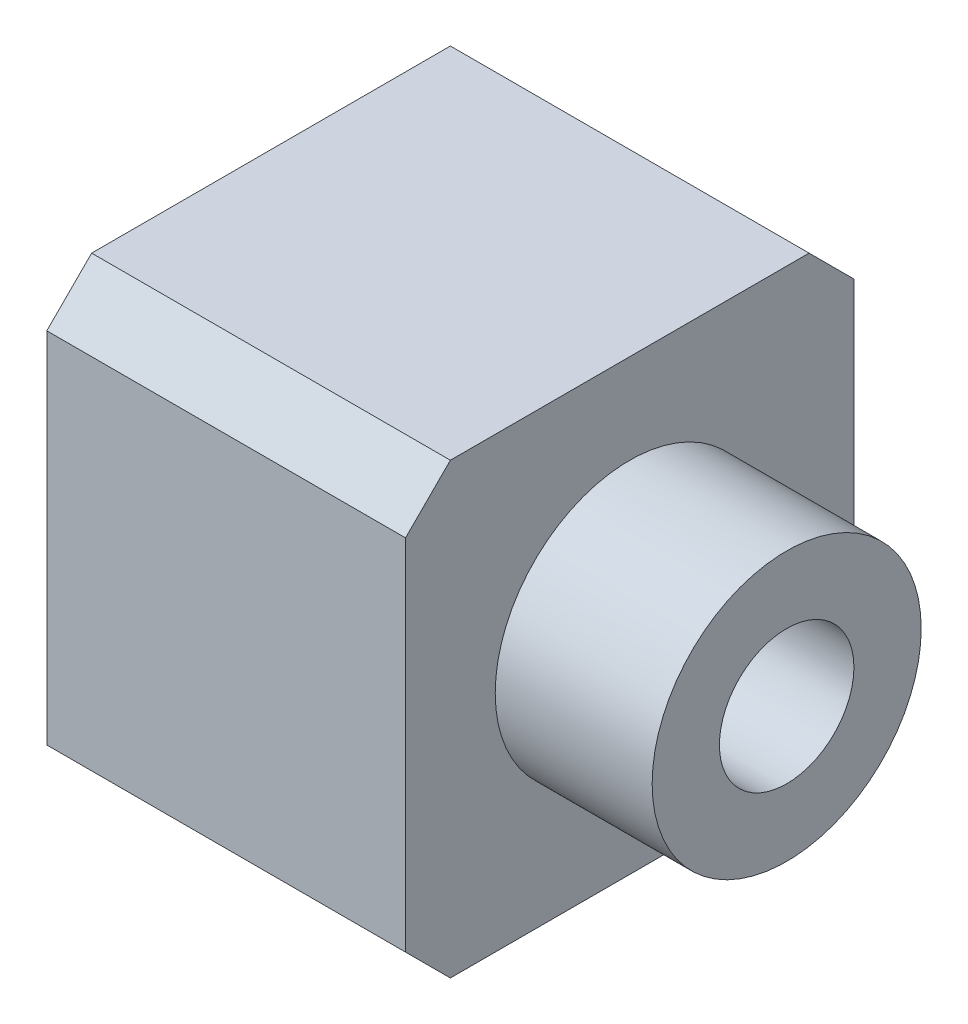
SolidWorks part; units mm, degrees
ref_plane "Front Plane" through (0, 0, 0) normal (0, 0, 1) x (1, 0, 0)
ref_plane "Top Plane" through (0, 0, 0) normal (0, 1, 0) x (1, 0, 0)
ref_plane "Right Plane" through (0, 0, 0) normal (1, 0, 0) x (0, 0, -1)
sketch "Sketch1" plane through (0, 0, 0) normal (1, 0, 0) x (0, 0, -1)
  line L5 (5, -5) -> (-5, -5)
  line L6 (5, -5) -> (5, 5)
  line L7 (5, 5) -> (-5, 5)
  line L8 (-5, -5) -> (-5, 5)
  line L9 (5, -5) -> (-5, 5) construction
  line L10 (5, 5) -> (-5, -5) construction
  point P0 (0, 0)
  dimension "D1" = 10
  dimension "D2" = 10
extrude "Boss-Extrude1" add sketch "Sketch1" against normal blind 13.5
sketch "Sketch2" plane through (0, 0, 0) normal (1, 0, 0) x (0, 0, -1)
  circle A0 centre (0, 0) radius 3
  circle A1 centre (0, 0) radius 15.3536
  dimension "D1" = 6
extrude "Cut-Extrude1" cut sketch "Sketch2" against normal blind 3.5
sketch "Sketch3" plane through (-13.5, 0, 0) normal (-1, 0, 0) x (0, 0, 1)
  circle A0 centre (0, 0) radius 3
  circle A1 centre (0, 0) radius 15.6354
  dimension "D1" = 6
extrude "Cut-Extrude2" cut sketch "Sketch3" against normal blind 2
sketch "Sketch4" plane through (0, 0, 0) normal (1, 0, 0) x (0, 0, -1)
  circle A0 centre (0, 0) radius 1.5
  dimension "D1" = 3
extrude "Cut-Extrude3" cut sketch "Sketch4" against normal through all
chamfer "Chamfer1" distance 1 angle 45 4 edges at (-7.5, -5, -5) (-7.5, 5, 5) (-7.5, -5, 5) (-7.5, 5, -5)
sketch "Sketch5" plane through (0, 0, 0) normal (0, 0, -1) x (-1, 0, 0)
  line L0 (0, 0) -> (7.5, 0) construction
  line L1 (0, 3) -> (0, -3) construction
  circle A0 centre (7.5, 0) radius 1.5
  dimension "D1" = 3
  dimension "D2" = 7.5
extrude "Cut-Extrude4" cut sketch "Sketch5" against normal blind 2 from offset 5
